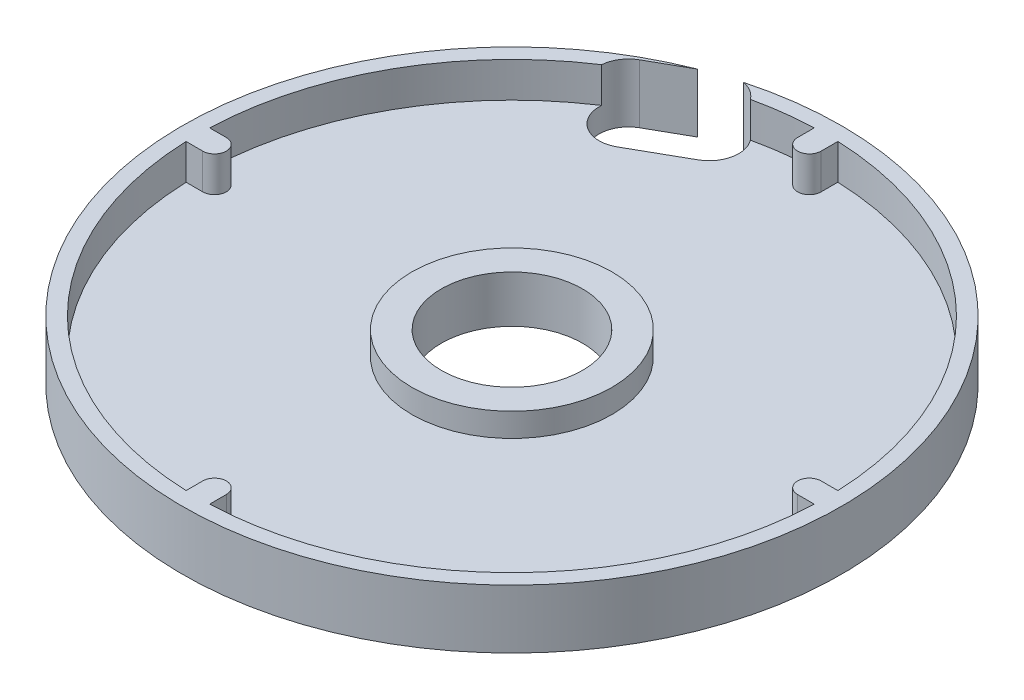
SolidWorks part; units mm, degrees
ref_plane "前视基准面" through (0, 0, 0) normal (0, 0, 1) x (1, 0, 0)
ref_plane "上视基准面" through (0, 0, 0) normal (0, 1, 0) x (1, 0, 0)
ref_plane "右视基准面" through (0, 0, 0) normal (1, 0, 0) x (0, 0, -1)
other "Configuration Table"
sketch "草图1" plane through (0, 0, 0) normal (0, 1, 0) x (1, 0, 0)
  circle A0 centre (0, 0) radius 28
  dimension "D1" = 56
extrude "凸台-拉伸1" add sketch "草图1" along normal blind 2
sketch "草图2" plane through (0, 2, 0) normal (0, 1, 0) x (1, 0, 0)
  circle A1 centre (0, 0) radius 26.7
  circle A2 centre (0, 0) radius 26.7
  circle A5 centre (0, 0) radius 28
  circle A6 centre (0, 0) radius 28
  dimension "D1" = 0
  dimension "D2" = 0
extrude "凸台-拉伸3" add sketch "草图2" along normal blind 3 contours A1 | A6
sketch "草图3" plane through (0, 2, 0) normal (0, 1, 0) x (1, 0, 0)
  line L0 (0, 28.6628) -> (0, 25.2628) construction
  line L1 (1, 26.6813) -> (1, 25.2628)
  line L2 (-1, 26.6813) -> (-1, 25.2628)
  arc A1 (-1, 25.2628) -> (1, 25.2628) centre (0, 25.2628) ccw
  circle A4 centre (0, 0) radius 26.7
  arc A5 (1, 26.6813) -> (-1, 26.6813) centre (0, 0) ccw
  point P2 (0, 26.9628)
  dimension "D2" = 1
  dimension "D1" = 1.7
  dimension "D3" = 0
extrude "凸台-拉伸4" add sketch "草图3" along normal blind 3
pattern_circular "阵列(圆周)1" count 4 over 360 about axis through (0, 0, 0) along (0, 1, 0) of "凸台-拉伸4"
sketch "草图4" plane through (0, 2, 0) normal (0, 1, 0) x (1, 0, 0)
  line L0 (0, 0) -> (0, 23.3317) construction
  line L1 (-12.1881, 22.095) -> (-7.8119, 24.5684) construction
  line L2 (-13.4182, 24.2714) -> (-9.0421, 26.7449)
  line L3 (-10.9579, 19.9185) -> (-6.5818, 22.392)
  arc A0 (-13.4182, 24.2714) -> (-10.9579, 19.9185) centre (-12.1881, 22.095) ccw
  arc A1 (-6.5818, 22.392) -> (-9.0421, 26.7449) centre (-7.8119, 24.5684) ccw
  point P5 (-10, 23.3317)
  dimension "D1" = 10
  dimension "D2" = 5
extrude "切除-拉伸1" cut sketch "草图4" against normal mid plane 10
sketch "草图5" plane through (0, 2, 0) normal (0, 1, 0) x (1, 0, 0)
  circle A0 centre (0, 0) radius 8.5
  circle A1 centre (0, 0) radius 6
extrude "凸台-拉伸5" add sketch "草图5" along normal blind 2
sketch "草图6" plane through (0, 2, 0) normal (0, 1, 0) x (1, 0, 0)
  circle A0 centre (0, 0) radius 6
extrude "切除-拉伸2" cut sketch "草图6" against normal mid plane 5
